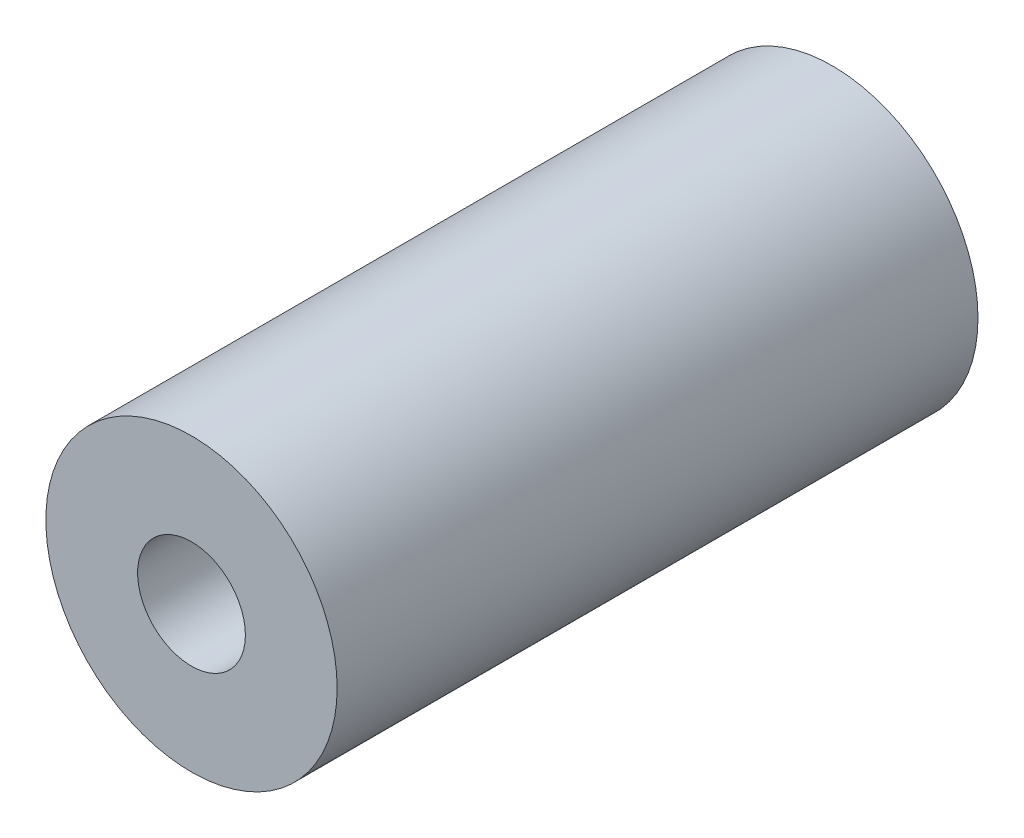
SolidWorks part; units mm, degrees
ref_plane "Front" through (0, 0, 0) normal (0, 0, 1) x (1, 0, 0)
ref_plane "Top" through (0, 0, 0) normal (0, 1, 0) x (1, 0, 0)
ref_plane "Right" through (0, 0, 0) normal (1, 0, 0) x (0, 0, -1)
sketch "Sketch1" plane through (0, 0, 0) normal (0, 0, 1) x (1, 0, 0)
  circle A0 centre (0, 0) radius 1.85
  circle A1 centre (0, 0) radius 5
extrude "Boss-Extrude1" add sketch "Sketch1" along normal blind 22
